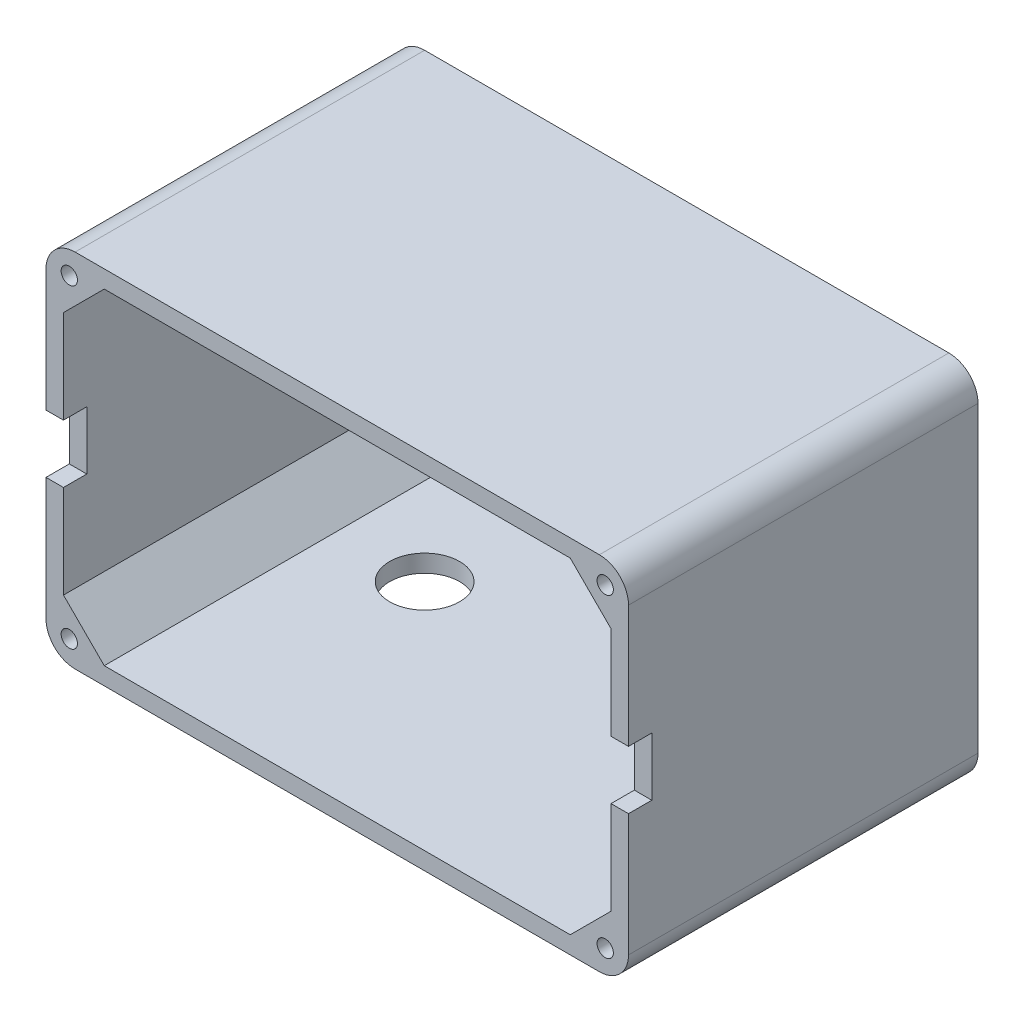
SolidWorks part; units mm, degrees
ref_plane "前视基准面" through (0, 0, 0) normal (0, 0, 1) x (1, 0, 0)
ref_plane "上视基准面" through (0, 0, 0) normal (0, 1, 0) x (1, 0, 0)
ref_plane "右视基准面" through (0, 0, 0) normal (1, 0, 0) x (0, 0, -1)
other "Configuration Table"
sketch "草图1" plane through (0, 0, 0) normal (0, 0, 1) x (1, 0, 0)
  line L1 (-45, 31) -> (45, 31)
  line L2 (-50, 26) -> (-50, -26)
  line L3 (-45, -31) -> (45, -31)
  line L4 (50, 26) -> (50, -26)
  line L5 (-50, 31) -> (50, -31) construction
  line L6 (-50, -31) -> (50, 31) construction
  line L7 (-42, 28) -> (42, 28)
  line L8 (-47, 23) -> (-47, -23)
  line L9 (-42, -28) -> (42, -28)
  line L10 (47, 23) -> (47, -23)
  line L11 (-47, 28) -> (47, -28) construction
  line L12 (-47, -28) -> (47, 28) construction
  arc A0 (-50, 26) -> (-45, 31) centre (-45, 26) cw
  arc A1 (50, 26) -> (45, 31) centre (45, 26) ccw
  arc A2 (45, -31) -> (50, -26) centre (45, -26) ccw
  arc A3 (-45, -31) -> (-50, -26) centre (-45, -26) cw
  arc A4 (-47, 23) -> (-42, 28) centre (-42, 23) cw
  arc A5 (47, 23) -> (42, 28) centre (42, 23) ccw
  arc A6 (42, -28) -> (47, -23) centre (42, -23) ccw
  arc A7 (-42, -28) -> (-47, -23) centre (-42, -23) cw
  point P0 (0, 0)
  point P18 (0, 0)
  dimension "D3" = 5
  dimension "D4" = 5
  dimension "D5" = 5
  dimension "D6" = 5
  dimension "D9" = 5
  dimension "D10" = 5
  dimension "D11" = 5
  dimension "D12" = 5
  dimension "D1" = 100
  dimension "D2" = 62
  dimension "D7" = 94
  dimension "D8" = 56
extrude "凸台-拉伸1" add sketch "草图1" along normal blind 60
sketch "草图3" plane through (0, 0, 60) normal (0, 0, 1) x (1, 0, 0)
  line L3 (-47, 28) -> (-47, 21)
  line L4 (-47, 23) -> (-47, -23) construction
  line L5 (-47, 21) -> (-40, 28)
  line L6 (42, 28) -> (-42, 28) construction
  line L7 (-40, 28) -> (-47, 28)
  dimension "D1" = 7
  dimension "D2" = 7
extrude "凸台-拉伸2" add sketch "草图3" against normal blind 60
sketch "草图4" plane through (0, 0, 60) normal (0, 0, 1) x (1, 0, 0)
  line L0 (45, 31) -> (-45, 31) construction
  line L1 (-50, 26) -> (-50, -26) construction
  circle A0 centre (-46, 27) radius 1.4
  dimension "D1" = 2.8
  dimension "D2" = 4
  dimension "D3" = 4
extrude "切除-拉伸1" cut sketch "草图4" against normal blind 60
mirror "镜向1" about plane through (0, 0, 0) normal (1, 0, 0) of "切除-拉伸1", "凸台-拉伸2"
mirror "镜向2" about plane through (0, 0, 0) normal (0, 1, 0) of "镜向1", "凸台-拉伸2", "切除-拉伸1"
sketch "草图7" plane through (0, -31, 0) normal (0, -1, 0) x (1, 0, 0)
  line L0 (0, 0) -> (0, 67.2879) construction
  line L1 (-45, 0) -> (45, 0) construction
  circle A0 centre (-25, 20) radius 6
  circle A1 centre (25, 20) radius 6
  dimension "D1" = 12
  dimension "D2" = 50
  dimension "D3" = 20
extrude "切除-拉伸3" cut sketch "草图7" against normal blind 10
sketch "草图8" plane through (50, 0, 0) normal (1, 0, 0) x (0, 0, -1)
  line L0 (-60, -26) -> (-60, 26) construction
  line L1 (-60, 5) -> (-56, 5)
  line L2 (-60, 5) -> (-60, -5)
  line L3 (-60, -5) -> (-56, -5)
  line L4 (-56, 5) -> (-56, -5)
  line L5 (0, 0) -> (-65.3917, 0) construction
  dimension "D1" = 10
  dimension "D2" = 4
  dimension "D3" = 5
extrude "切除-拉伸4" cut sketch "草图8" against normal blind 100
